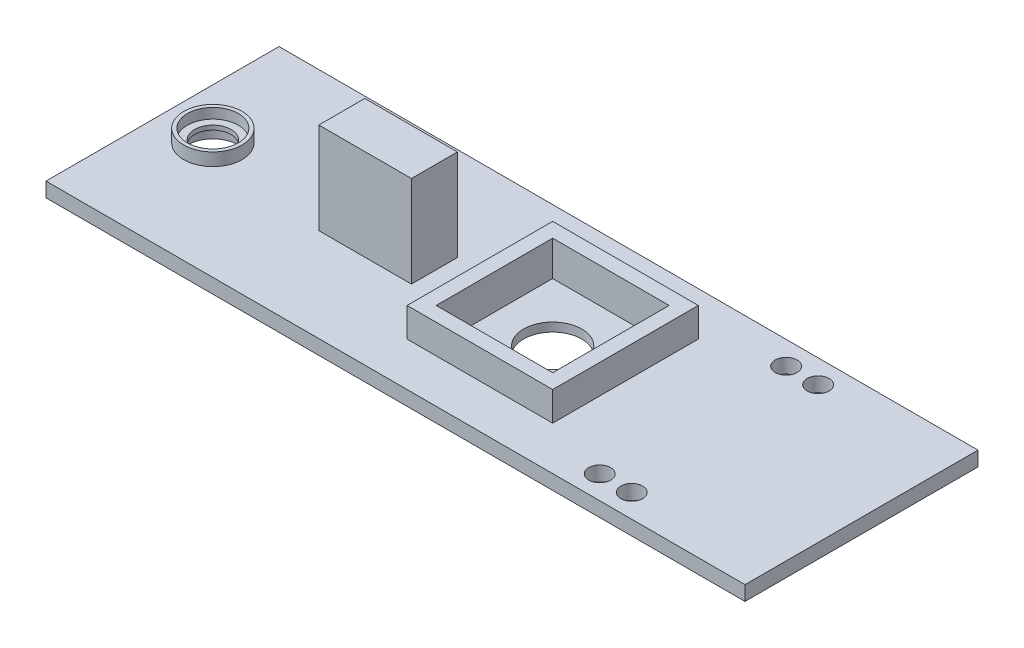
SolidWorks part; units mm, degrees
ref_plane "Front Plane" through (0, 0, 0) normal (0, 0, 1) x (1, 0, 0)
ref_plane "Top Plane" through (0, 0, 0) normal (0, 1, 0) x (1, 0, 0)
ref_plane "Right Plane" through (0, 0, 0) normal (1, 0, 0) x (0, 0, -1)
sketch "Sketch1" plane through (0, 0, 0) normal (0, 1, 0) x (1, 0, 0)
  line L1 (-304.8, -50.8) -> (0, -50.8)
  line L2 (-304.8, -50.8) -> (-304.8, 50.8)
  line L3 (-304.8, 50.8) -> (0, 50.8)
  line L4 (0, -50.8) -> (0, 50.8)
  point P0 (0, 0)
  dimension "D1" = 304.8
  dimension "D2" = 101.6
extrude "Boss-Extrude1" add sketch "Sketch1" along normal blind 6.35
sketch "Sketch2" plane through (0, 6.35, 0) normal (0, 1, 0) x (1, 0, 0)
  circle A0 centre (-282.8392, 0) radius 12.7
  point P2 (-282.8392, 0)
extrude "Boss-Extrude3" add sketch "Sketch2" along normal blind 5.5562
sketch "Sketch9" plane through (0, 11.9062, 0) normal (0, 1, 0) x (1, 0, 0)
  circle A0 centre (-282.8392, 0) radius 11.1125
extrude "Cut-Extrude4" cut sketch "Sketch9" against normal blind 4.445
sketch "Sketch10" plane through (0, 0, 0) normal (0, -1, 0) x (-1, 0, 0)
  circle A0 centre (282.8392, 0) radius 11.1125
extrude "Cut-Extrude5" cut sketch "Sketch10" against normal blind 5.5562
sketch "Sketch11" plane through (0, 7.4613, 0) normal (0, 1, 0) x (1, 0, 0)
  circle A0 centre (-282.8392, 0) radius 7.9375
extrude "Cut-Extrude6" cut sketch "Sketch11" against normal through all
sketch "Sketch12" plane through (0, 6.35, 0) normal (0, 1, 0) x (1, 0, 0)
  circle A0 centre (-134.6662, 0) radius 12.7
  dimension "D1" = 25.4
extrude "Cut-Extrude7" cut sketch "Sketch12" against normal through all
sketch "Sketch22" plane through (0, 6.35, 0) normal (0, 1, 0) x (1, 0, 0)
  line L1 (-102.9162, -31.75) -> (-166.4162, -31.75)
  line L2 (-102.9162, -31.75) -> (-102.9162, 31.75)
  line L3 (-102.9162, 31.75) -> (-166.4162, 31.75)
  line L4 (-166.4162, -31.75) -> (-166.4162, 31.75)
  line L5 (-102.9162, -31.75) -> (-166.4162, 31.75) construction
  line L6 (-102.9162, 31.75) -> (-166.4162, -31.75) construction
  circle A0 centre (-134.6662, 0) radius 12.7 construction
  point P0 (-134.6662, 0)
extrude "Boss-Extrude7" add sketch "Sketch22" along normal blind 12.7
sketch "Sketch25" plane through (0, 19.05, 0) normal (0, 1, 0) x (1, 0, 0)
  line L1 (-109.2662, -25.4) -> (-160.0662, -25.4)
  line L2 (-109.2662, -25.4) -> (-109.2662, 25.4)
  line L3 (-109.2662, 25.4) -> (-160.0662, 25.4)
  line L4 (-160.0662, -25.4) -> (-160.0662, 25.4)
  line L5 (-109.2662, -25.4) -> (-160.0662, 25.4) construction
  line L6 (-109.2662, 25.4) -> (-160.0662, -25.4) construction
  circle A0 centre (-134.6662, 0) radius 12.7 construction
  point P0 (-134.6662, 0)
  dimension "D1" = 50.8
  dimension "D2" = 50.8
extrude "Cut-Extrude11" cut sketch "Sketch25" against normal blind 15.24
sketch "Sketch18" plane through (0, 6.35, 0) normal (0, 1, 0) x (1, 0, 0)
  line L2 (-226.612, -10.033) -> (-186.226, -10.033)
  line L3 (-226.612, -10.033) -> (-226.612, 10.033)
  line L4 (-226.612, 10.033) -> (-186.226, 10.033)
  line L5 (-186.226, -10.033) -> (-186.226, 10.033)
extrude "Boss-Extrude5" add sketch "Sketch18" along normal blind 39.878 contours L3 L2 L5 L4
sketch "Sketch32" plane through (0, 6.35, 0) normal (0, 1, 0) x (1, 0, 0)
  line L1 (-304.8, -50.8) -> (0, -50.8) construction
  line L2 (0, 50.8) -> (-304.8, 50.8) construction
  circle A0 centre (-59.5449, -40.64) radius 4.7625
  circle A1 centre (-73.5149, -40.64) radius 4.7625
  circle A2 centre (-59.5449, 40.64) radius 4.7625
  circle A3 centre (-73.5149, 40.64) radius 4.7625
  point P12 (0, 0)
  point P13 (-46.9267, -40.64)
  point P14 (-32.9567, 40.64)
  point P15 (-21.59, -42.8938)
  point P16 (-46.9267, 40.64)
  point P17 (-64.3865, -40.64)
  point P18 (-73.5149, -40.64)
  dimension "D1" = 10.16
  dimension "D2" = 10.16
  dimension "D3" = 10.16
  dimension "D4" = 10.16
  dimension "D5" = 13.97
  dimension "D6" = 13.97
  dimension "D7" = 81.28
extrude "Cut-Extrude12" cut sketch "Sketch32" against normal blind 6.35
sketch "Sketch38" plane through (0, 6.35, 0) normal (0, 1, 0) x (1, 0, 0)
  line L1 (-88.3974, -10.9426) -> (-41.3975, -10.9426)
  line L2 (-88.3974, -10.9426) -> (-88.3974, 24.0574)
  line L3 (-88.3974, 24.0574) -> (-41.3975, 24.0574)
  line L4 (-41.3975, -10.9426) -> (-41.3975, 24.0574)
sketch "Sketch34" plane through (0, 6.35, 0) normal (0, 1, 0) x (1, 0, 0)
  line L0 (0, -50.8) -> (0, 50.8) construction
  line L1 (0, -34.0128) -> (-39.7447, -34.0128)
  line L2 (0, -34.0128) -> (0, -16.8526)
  line L3 (0, -16.8526) -> (-39.7447, -16.8526)
  line L4 (-39.7447, -34.0128) -> (-39.7447, -16.8526)
  line L5 (-304.8, -50.8) -> (0, -50.8) construction
  dimension "D1" = 16.7872
